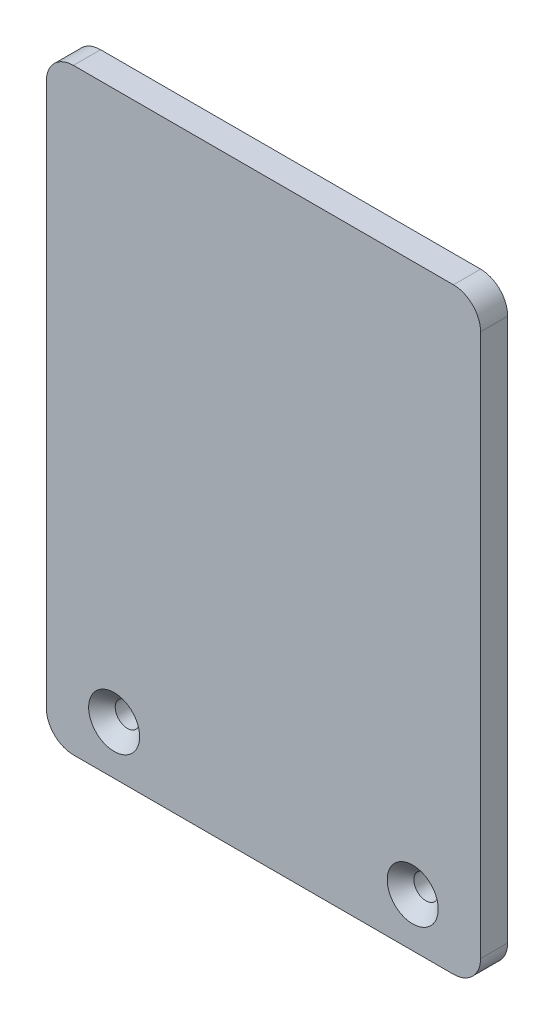
SolidWorks part; units mm, degrees
ref_plane "Plano frontal" through (0, 0, 0) normal (0, 0, 1) x (1, 0, 0)
ref_plane "Plano superior" through (0, 0, 0) normal (0, 1, 0) x (1, 0, 0)
ref_plane "Plano direito" through (0, 0, 0) normal (1, 0, 0) x (0, 0, -1)
sketch "Sketch1" plane through (0, 0, 0) normal (0, 0, 1) x (1, 0, 0)
  line L1 (-40, 0) -> (40, 0)
  line L2 (-40, 0) -> (-40, 110)
  line L3 (-40, 110) -> (40, 110)
  line L4 (40, 0) -> (40, 110)
  line L5 (0, 110) -> (0, 0) construction
  line L6 (-40, 55) -> (40, 55) construction
  point P276 (0, 55)
  dimension "D1" = 80
  dimension "D2" = 110
extrude "Boss-Extrude1" add sketch "Sketch1" along normal blind 5
fillet "Fillet1" radius 5 4 edges at (40, 110, 2.5) (-40, 110, 2.5) (-40, 0, 2.5) (40, 0, 2.5)
hole_wizard "CSK for M4 Countersunk Flat Head Screw1" positions "Sketch3" profile "Sketch2" countersink size "M4" standard "DIN"
sketch "Sketch3" plane through (0, 0, 5) normal (0, 0, 1) x (1, 0, 0)
  line L0 (-35, 0) -> (35, 0) construction
  line L1 (-27.5, 9) -> (27.5, 8.9874) construction
  line L4 (0, 8.9937) -> (0, 0) construction
  point P0 (-27.5, 9)
  point P2 (27.5, 8.9874)
  dimension "D1" = 9
  dimension "D2" = 55
sketch "Sketch2" plane through (-27.5, 9, 5) normal (1, 0, 0) x (0, -1, 0)
  line L0 (0, 0) -> (0, 11.3519)
  line L1 (0, 11.3519) -> (2.25, 10)
  line L2 (2.25, 10) -> (2.25, 2.45)
  line L3 (2.25, 2.45) -> (4.7, 0)
  line L5 (4.7, 0) -> (0, 0)
  line L6 (-2.25, 2.45) -> (-4.7, 0) construction
  line L10 (0, 11.3519) -> (-2.25, 10) construction
  line L11 (0, -6.35) -> (0, 107.95) construction
  dimension "Hole Dia." = 4.5
  dimension "Hole Depth" = 10
  dimension "Near C'Sink Dia." = 9.4
  dimension "Near C'Sink Angle" = 90
  dimension "Drill Angle" = 118
